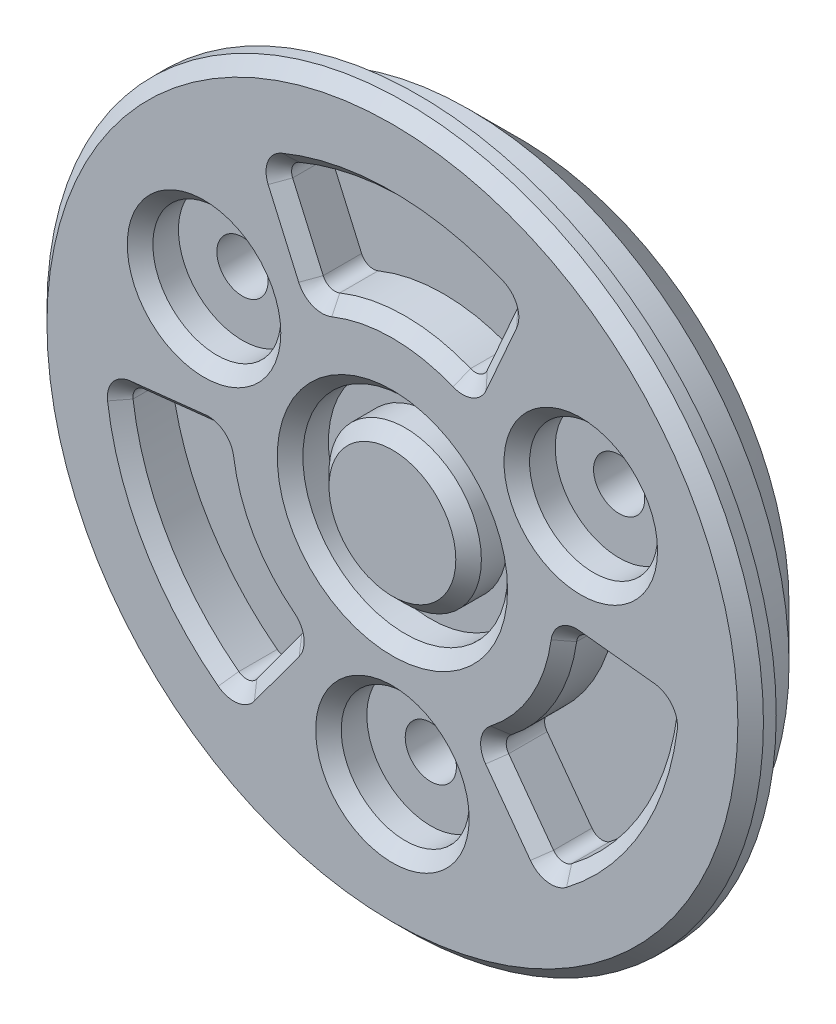
SolidWorks part; units mm, degrees
ref_plane "Front Plane" through (0, 0, 0) normal (0, 0, 1) x (1, 0, 0)
ref_plane "Top Plane" through (0, 0, 0) normal (0, 1, 0) x (1, 0, 0)
ref_plane "Right Plane" through (0, 0, 0) normal (1, 0, 0) x (0, 0, -1)
other "Configuration Table"
sketch "草图4" plane through (0, 0, 20.1167) normal (0, 0, 1) x (1, 0, 0)
  circle A0 centre (0.1738, -3.1409) radius 12.5
extrude "凸台-拉伸1" add sketch "草图4" against normal blind 4
sketch "草图5" plane through (0, 0, 16.1167) normal (0, 0, -1) x (-1, 0, 0)
  circle A0 centre (-0.1738, -3.1409) radius 2.5
  circle A1 centre (-0.1738, -3.1409) radius 12.5 construction
extrude "切除-拉伸1" cut sketch "草图5" against normal blind 3
sketch "草图6" plane through (0, 0, 20.1167) normal (0, 0, 1) x (1, 0, 0)
  circle A0 centre (0.1738, -3.1409) radius 14
extrude "凸台-拉伸2" add sketch "草图6" along normal blind 1
sketch "草图7" plane through (0, 0, 16.1167) normal (0, 0, -1) x (-1, 0, 0)
  line L0 (-0.1738, 5.3591) -> (-0.1738, -3.1409) construction
  circle A0 centre (-0.1738, 5.3591) radius 1
  circle A11 centre (7.1875, 1.1091) radius 1
  circle A12 centre (7.1875, -7.3909) radius 1
  circle A13 centre (-0.1738, -11.6409) radius 1
  circle A14 centre (-7.535, -7.3909) radius 1
  circle A15 centre (-7.535, 1.1091) radius 1
  point P16 (0.1738, -3.1409)
  point P17 (-0.1738, -3.1409)
  dimension "D1" = 6
extrude "切除-拉伸2" cut sketch "草图7" against normal blind 2
sketch "草图11" plane through (0, 0, 21.1167) normal (0, 0, 1) x (1, 0, 0)
  circle A0 centre (0.1738, -11.6409) radius 1
  circle A1 centre (-7.1875, 1.1091) radius 1
  circle A2 centre (7.535, 1.1091) radius 1
extrude "切除-拉伸5" cut sketch "草图11" against normal through all
sketch "草图13" plane through (0, 0, 21.1167) normal (0, 0, 1) x (1, 0, 0)
  circle A0 centre (0.1738, -3.1409) radius 2.9772
  circle A1 centre (0.1738, -3.1409) radius 4
  circle A2 centre (0.1738, -11.6409) radius 2.5
  circle A3 centre (-7.1875, 1.1091) radius 2.5
  circle A4 centre (7.535, 1.1091) radius 2.5
extrude "切除-拉伸6" cut sketch "草图13" against normal blind 1.5
sketch "草图15" plane through (0, 0, 21.1167) normal (0, 0, 1) x (1, 0, 0)
  line L0 (0.1738, -11.6409) -> (-7.1875, 1.1091) construction
  line L1 (-7.1875, 1.1091) -> (7.535, 1.1091) construction
  line L2 (7.535, 1.1091) -> (-5.9681, -6.6869) construction
  line L3 (-5.6228, -11.5654) -> (-3.871, -9.1762)
  line L4 (-10.0204, -3.9487) -> (-7.0753, -3.6261)
  line L5 (-4.2238, 6.0913) -> (-3.0306, 3.3796)
  line L6 (4.5713, 6.0913) -> (3.3781, 3.3796)
  line L7 (10.3679, -3.9487) -> (7.4229, -3.6261)
  line L8 (5.9704, -11.5654) -> (4.2185, -9.1762)
  arc A0 (-6.5255, -4.0555) -> (-3.9679, -8.4853) centre (0.1738, -3.1409) ccw
  arc A1 (-10.4619, -4.5095) -> (-6.3293, -11.6674) centre (0.1738, -3.1409) ccw
  arc A2 (-3.9679, -8.4853) -> (-3.871, -9.1762) centre (-4.2742, -8.8806) cw
  arc A3 (-5.6228, -11.5654) -> (-6.3293, -11.6674) centre (-6.0261, -11.2698) cw
  arc A4 (-10.0204, -3.9487) -> (-10.4619, -4.5095) centre (-9.966, -4.4457) ccw
  arc A5 (-6.5255, -4.0555) -> (-7.0753, -3.6261) centre (-7.0209, -4.1232) ccw
  arc A6 (2.7313, 3.1181) -> (-2.3838, 3.1181) centre (0.1738, -3.1409) ccw
  arc A7 (4.3064, 6.7541) -> (-3.9588, 6.7541) centre (0.1738, -3.1409) ccw
  arc A8 (-2.3838, 3.1181) -> (-3.0306, 3.3796) centre (-2.5729, 3.581) cw
  arc A9 (-4.2238, 6.0913) -> (-3.9588, 6.7541) centre (-3.7661, 6.2927) cw
  arc A10 (4.5713, 6.0913) -> (4.3064, 6.7541) centre (4.1137, 6.2927) ccw
  arc A11 (2.7313, 3.1181) -> (3.3781, 3.3796) centre (2.9204, 3.581) ccw
  arc A12 (4.3155, -8.4853) -> (6.873, -4.0555) centre (0.1738, -3.1409) ccw
  arc A13 (6.6768, -11.6674) -> (10.8094, -4.5095) centre (0.1738, -3.1409) ccw
  arc A14 (6.873, -4.0555) -> (7.4229, -3.6261) centre (7.3684, -4.1232) cw
  arc A15 (10.3679, -3.9487) -> (10.8094, -4.5095) centre (10.3135, -4.4457) cw
  arc A16 (5.9704, -11.5654) -> (6.6768, -11.6674) centre (6.3736, -11.2698) ccw
  arc A17 (4.3155, -8.4853) -> (4.2185, -9.1762) centre (4.6217, -8.8806) ccw
  point P48 (0.1738, -3.1409)
  dimension "D1" = 3
extrude "切除-拉伸7" cut sketch "草图15" against normal blind 2
chamfer "倒角2" distance 0.5 angle 45 30 edges at (6.0293, -6.5216, 21.1167) (4.1266, -8.8111, 21.1167) (5.0944, -10.3708, 21.1167) (6.3022, -11.7647, 21.1167) (9.4604, -8.5026, 21.1167) (10.7064, -4.1364, 21.1167) (8.8954, -3.7874, 21.1167) (7.0607, -3.7291, 21.1167) (-5.6818, -6.5216, 21.1167) (-6.7131, -3.7291, 21.1167) (-8.5479, -3.7874, 21.1167) (-10.3588, -4.1364, 21.1167) (-9.1129, -8.5026, 21.1167) (-5.9547, -11.7647, 21.1167) (-4.7469, -10.3708, 21.1167) (-3.7791, -8.8111, 21.1167) (10.035, 1.1091, 21.1167) (-4.6875, 1.1091, 21.1167) (2.6738, -11.6409, 21.1167) (4.1738, -3.1409, 21.1167) (14.1738, -3.1409, 21.1167) (0.1738, 3.6205, 21.1167) (3.1078, 3.1174, 21.1167) (3.9747, 4.7355, 21.1167) (4.5779, 6.4783, 21.1167) (0.1738, 7.5824, 21.1167) (-4.2304, 6.4783, 21.1167) (-3.6272, 4.7355, 21.1167) (-2.7603, 3.1174, 21.1167) (3.151, -3.1409, 21.1167)
fillet "圆角1" radius 2 1 edges at (12.6738, -3.1409, 16.1167) profile chamfer
sketch "草图16" plane through (0, 0, 16.1167) normal (0, 0, -1) x (-1, 0, 0)
  circle A0 centre (-0.1738, -3.1409) radius 3.5
extrude "切除-拉伸8" cut sketch "草图16" against normal blind 0.5
